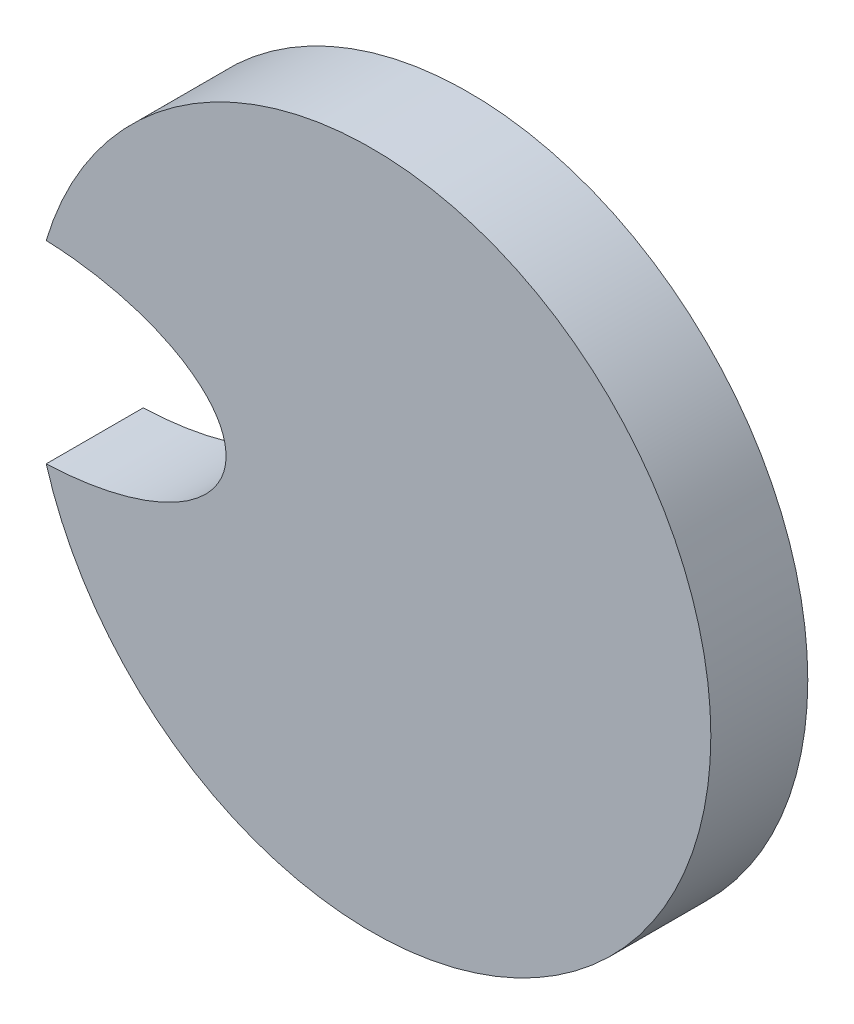
SolidWorks part; units mm, degrees
ref_plane "Top Plane" through (0, 0, 0) normal (0, 0, 1) x (1, 0, 0)
ref_plane "Right Plane" through (0, 0, 0) normal (0, 1, 0) x (1, 0, 0)
ref_plane "Front Plane" through (0, 0, 0) normal (1, 0, 0) x (0, 0, -1)
sketch "Sketch1" plane through (0, 0, 0) normal (0, 0, 1) x (1, 0, 0)
  circle A0 centre (0, 0) radius 35
extrude "Boss-Extrude1" add sketch "Sketch1" along normal blind 10
sketch "Sketch2" plane through (0, 0, 10) normal (0, 0, 1) x (1, 0, 0)
  circle A0 centre (0, 0) radius 35 construction
  ellipse E0 centre (-35, 0) end of major axis (-15, 0) minor radius 10
extrude "Cut-Extrude1" cut sketch "Sketch2" against normal blind 20
